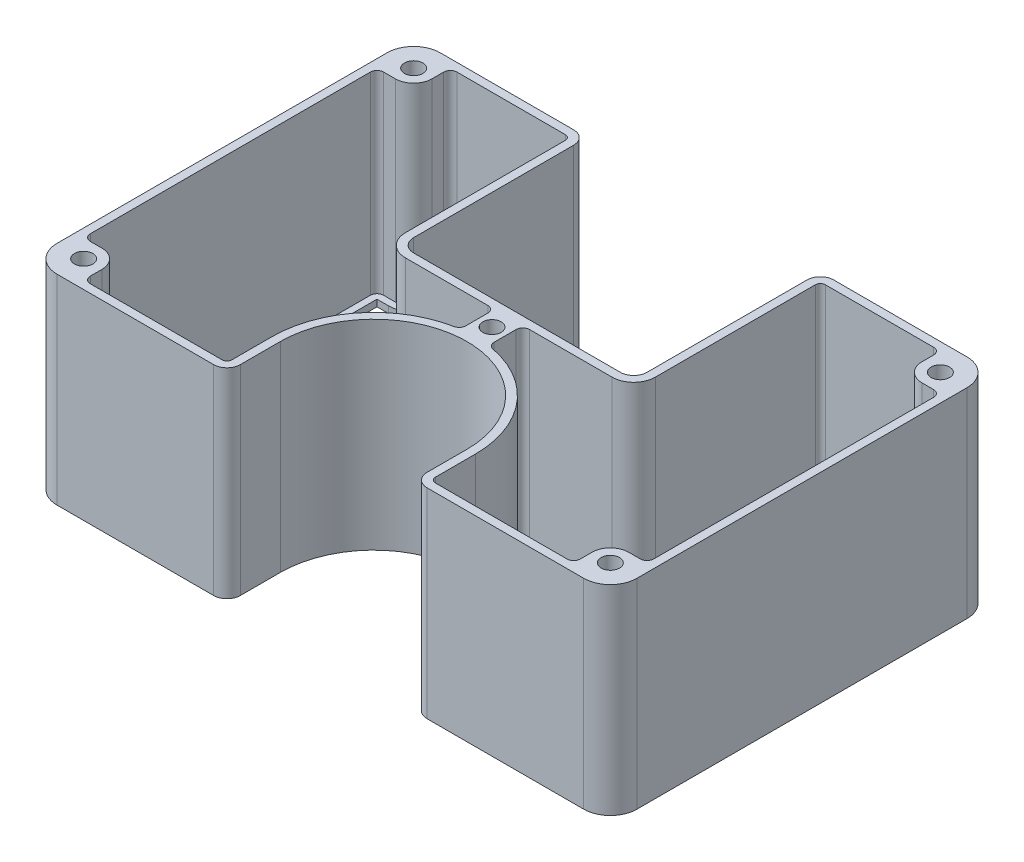
SolidWorks part; units mm, degrees
material "ABS"
ref_plane "Front Plane" through (0, 0, 0) normal (0, 0, 1) x (1, 0, 0)
ref_plane "Top Plane" through (0, 0, 0) normal (0, 1, 0) x (1, 0, 0)
ref_plane "Right Plane" through (0, 0, 0) normal (1, 0, 0) x (0, 0, -1)
sketch "Reference" plane through (0, 0, 0) normal (0, 1, 0) x (1, 0, 0)
  line L0 (-79, -96) -> (79, -96) construction
  line L1 (87, -88) -> (87, 88) construction
  line L2 (79, 96) -> (-79, 96) construction
  line L3 (-87, 88) -> (-87, -88) construction
  circle A0 centre (0, -3) radius 16.25 construction
  arc A1 (-79, -96) -> (-87, -88) centre (-79, -88) cw construction
  arc A2 (79, -96) -> (87, -88) centre (79, -88) ccw construction
  arc A3 (87, 88) -> (79, 96) centre (79, 88) ccw construction
  arc A4 (-79, 96) -> (-87, 88) centre (-79, 88) ccw construction
  circle A5 centre (-65, 78) radius 1.75 construction
  circle A6 centre (65, 78) radius 1.75 construction
  circle A7 centre (65, -78) radius 1.75 construction
  circle A8 centre (-65, -78) radius 1.75 construction
  point P6 (0, -96)
  dimension "D1" = 32.5
  dimension "D3" = 8
  dimension "D4" = 3.5
  dimension "D2" = 93
  dimension "D5" = 130
  dimension "D6" = 22
  dimension "D7" = 22
  dimension "D8" = 156
  dimension "D9" = 18
  dimension "D10" = 18
sketch "Sketch2" plane through (0, 0, 0) normal (0, 1, 0) x (1, 0, 0)
  line L0 (87, -88) -> (87, 88) construction
  line L1 (-87, 88) -> (-87, -88) construction
  line L2 (79, 96) -> (-79, 96) construction
  line L3 (87, -11) -> (87, 88)
  line L4 (-87, 88) -> (-87, -11)
  line L5 (79, 96) -> (39, 96)
  line L6 (-79, -19) -> (-32, -19)
  line L7 (79, -19) -> (32, -19)
  line L8 (-28, -15) -> (-28, -3)
  line L9 (28, -15) -> (28, -3)
  line L10 (-35, 92) -> (-35, 44)
  line L11 (-31, 40) -> (31, 40)
  line L12 (35, 44) -> (35, 92)
  line L13 (-39, 96) -> (-79, 96)
  line L14 (-39, 93.5) -> (-71.5, 93.5)
  line L15 (-84.5, 80.5) -> (-84.5, -3.5)
  line L16 (-71.5, -16.5) -> (-32, -16.5)
  line L17 (-30.5, -15) -> (-30.5, -3)
  line L18 (30.5, -15) -> (30.5, -3)
  line L19 (71.5, -16.5) -> (32, -16.5)
  line L20 (84.5, -3.5) -> (84.5, 80.5)
  line L21 (71.5, 93.5) -> (39, 93.5)
  line L22 (37.5, 44) -> (37.5, 92)
  line L23 (-31, 37.5) -> (-6.25, 37.5)
  line L24 (-37.5, 92) -> (-37.5, 44)
  line L25 (-79, 82.5) -> (-82.5, 82.5)
  line L26 (-73.5, 88) -> (-73.5, 91.5)
  line L27 (-39, 93.5) -> (-79, 93.5) construction
  line L28 (-84.5, 88) -> (-84.5, -11) construction
  line L29 (73.5, 88) -> (73.5, 91.5)
  line L30 (79, 82.5) -> (82.5, 82.5)
  line L31 (84.5, -11) -> (84.5, 88) construction
  line L32 (79, 93.5) -> (39, 93.5) construction
  line L33 (-79, -5.5) -> (-82.5, -5.5)
  line L34 (-73.5, -11) -> (-73.5, -14.5)
  line L35 (-79, -16.5) -> (-32, -16.5) construction
  line L36 (79, -5.5) -> (82.5, -5.5)
  line L37 (73.5, -11) -> (73.5, -14.5)
  line L38 (79, -16.5) -> (32, -16.5) construction
  line L39 (-4.25, 35.5) -> (-4.25, 28.8934)
  line L40 (4.25, 35.5) -> (4.25, 28.8934)
  line L41 (6.25, 37.5) -> (31, 37.5)
  line L42 (-31, 37.5) -> (31, 37.5) construction
  arc A0 (87, -11) -> (79, -19) centre (79, -11) cw
  arc A1 (87, 88) -> (79, 96) centre (79, 88) ccw construction
  arc A2 (-79, 96) -> (-87, 88) centre (-79, 88) ccw construction
  arc A4 (87, 88) -> (79, 96) centre (79, 88) ccw
  arc A5 (-79, 96) -> (-87, 88) centre (-79, 88) ccw
  arc A6 (-87, -11) -> (-79, -19) centre (-79, -11) ccw
  circle A7 centre (0, -3) radius 25 construction
  arc A8 (-28, -3) -> (28, -3) centre (0, -3) cw
  arc A9 (31, 40) -> (35, 44) centre (31, 44) ccw
  arc A10 (-35, 44) -> (-31, 40) centre (-31, 44) ccw
  arc A11 (35, 92) -> (39, 96) centre (39, 92) cw
  arc A12 (-35, 92) -> (-39, 96) centre (-39, 92) ccw
  arc A13 (32, -19) -> (28, -15) centre (32, -15) cw
  arc A14 (-32, -19) -> (-28, -15) centre (-32, -15) ccw
  arc A17 (-32, -16.5) -> (-30.5, -15) centre (-32, -15) ccw
  arc A18 (-30.5, -3) -> (-5.8654, 26.9307) centre (0, -3) cw
  arc A19 (32, -16.5) -> (30.5, -15) centre (32, -15) cw
  arc A22 (37.5, 92) -> (39, 93.5) centre (39, 92) cw
  arc A23 (31, 37.5) -> (37.5, 44) centre (31, 44) ccw
  arc A24 (-37.5, 44) -> (-31, 37.5) centre (-31, 44) ccw
  arc A25 (-37.5, 92) -> (-39, 93.5) centre (-39, 92) ccw
  circle A26 centre (-79, 88) radius 2.75
  circle A27 centre (79, 88) radius 2.75
  circle A28 centre (79, -11) radius 2.75
  circle A29 centre (-79, -11) radius 2.75
  arc A31 (-79, 82.5) -> (-73.5, 88) centre (-79, 88) ccw
  arc A32 (73.5, 88) -> (79, 82.5) centre (79, 88) ccw
  arc A33 (79, -5.5) -> (73.5, -11) centre (79, -11) ccw
  arc A34 (-73.5, -11) -> (-79, -5.5) centre (-79, -11) ccw
  arc A35 (-79, 93.5) -> (-84.5, 88) centre (-79, 88) ccw construction
  arc A36 (84.5, 88) -> (79, 93.5) centre (79, 88) ccw construction
  arc A37 (-84.5, -11) -> (-79, -16.5) centre (-79, -11) ccw construction
  arc A38 (84.5, -11) -> (79, -16.5) centre (79, -11) cw construction
  arc A39 (82.5, 82.5) -> (84.5, 80.5) centre (82.5, 80.5) cw
  arc A40 (73.5, 91.5) -> (71.5, 93.5) centre (71.5, 91.5) ccw
  arc A41 (-73.5, 91.5) -> (-71.5, 93.5) centre (-71.5, 91.5) cw
  arc A42 (-82.5, 82.5) -> (-84.5, 80.5) centre (-82.5, 80.5) ccw
  arc A43 (82.5, -5.5) -> (84.5, -3.5) centre (82.5, -3.5) ccw
  arc A44 (73.5, -14.5) -> (71.5, -16.5) centre (71.5, -14.5) cw
  arc A45 (-73.5, -14.5) -> (-71.5, -16.5) centre (-71.5, -14.5) ccw
  arc A46 (-82.5, -5.5) -> (-84.5, -3.5) centre (-82.5, -3.5) cw
  circle A47 centre (0, 32.5) radius 2.75
  arc A48 (5.8654, 26.9307) -> (30.5, -3) centre (0, -3) cw
  arc A49 (-30.5, -3) -> (30.5, -3) centre (0, -3) cw construction
  arc A50 (4.25, 35.5) -> (6.25, 37.5) centre (6.25, 35.5) cw
  arc A51 (4.25, 28.8934) -> (5.8654, 26.9307) centre (6.25, 28.8934) ccw
  arc A52 (-4.25, 28.8934) -> (-5.8654, 26.9307) centre (-6.25, 28.8934) cw
  arc A53 (-4.25, 35.5) -> (-6.25, 37.5) centre (-6.25, 35.5) ccw
  point P0 (0, -3)
  point P35 (-35, 96)
  point P38 (28, -19)
  point P41 (-28, -19)
  point P121 (4.25, 37.5)
  point P124 (4.25, 27.2024)
  point P129 (0, 25)
  point P131 (0, 40)
  dimension "D2" = 8
  dimension "D3" = 4
  dimension "D6" = 2
  dimension "D7" = 2
  dimension "D17" = 5.5
  dimension "D1" = 56
  dimension "D4" = 70
  dimension "D9" = 4.25
  dimension "D10" = 4.25
  dimension "D11" = 15
  dimension "D8" = 7.5
  dimension "D12" = 115
  dimension "D13" = 8
  dimension "D14" = 8
  dimension "D15" = 99
  dimension "D16" = 44
  dimension "D18" = 51.5
  dimension "D5" = 2.5
extrude "Boss-Extrude1" add sketch "Sketch2" along normal blind 60
sketch "Sketch3" plane through (0, 0, 0) normal (0, -1, 0) x (1, 0, 0)
  line L22 (71.5, 14.5) -> (32.5, 14.5)
  line L23 (71.5, 11) -> (71.5, 14.5)
  line L24 (82.5, 3.5) -> (79, 3.5)
  line L25 (82.5, -80.5) -> (82.5, 3.5)
  line L26 (79, -80.5) -> (82.5, -80.5)
  line L27 (71.5, -91.5) -> (71.5, -88)
  line L28 (39.5, -91.5) -> (71.5, -91.5)
  line L29 (39.5, -44) -> (39.5, -91.5)
  line L30 (6.25, -35.5) -> (31, -35.5)
  line L31 (6.25, -28.8934) -> (6.25, -35.5)
  line L32 (71.5, 14.5) -> (32.5, 14.5)
  line L33 (71.5, 11) -> (71.5, 14.5)
  line L34 (82.5, 3.5) -> (79, 3.5)
  line L35 (82.5, -80.5) -> (82.5, 3.5)
  line L36 (79, -80.5) -> (82.5, -80.5)
  line L37 (71.5, -91.5) -> (71.5, -88)
  line L38 (39.5, -91.5) -> (71.5, -91.5)
  line L39 (39.5, -44) -> (39.5, -91.5)
  line L40 (6.25, -35.5) -> (31, -35.5)
  line L41 (6.25, -28.8934) -> (6.25, -35.5)
  line L42 (30.5, 15) -> (30.5, 3)
  line L43 (71.5, 16.5) -> (32, 16.5)
  line L44 (73.5, 11) -> (73.5, 14.5)
  line L45 (-39.5, -91.5) -> (-39.5, -44)
  line L46 (-71.5, -91.5) -> (-39.5, -91.5)
  line L47 (-71.5, -88) -> (-71.5, -91.5)
  line L48 (-82.5, -80.5) -> (-79, -80.5)
  line L49 (-82.5, 3.5) -> (-82.5, -80.5)
  line L50 (-79, 3.5) -> (-82.5, 3.5)
  line L51 (-71.5, 14.5) -> (-71.5, 11)
  line L52 (-32.5, 14.5) -> (-71.5, 14.5)
  line L53 (-6.25, -35.5) -> (-6.25, -28.8934)
  line L54 (-31, -35.5) -> (-6.25, -35.5)
  line L55 (-39.5, -91.5) -> (-39.5, -44)
  line L56 (-71.5, -91.5) -> (-39.5, -91.5)
  line L57 (-71.5, -88) -> (-71.5, -91.5)
  line L58 (-82.5, -80.5) -> (-79, -80.5)
  line L59 (-82.5, 3.5) -> (-82.5, -80.5)
  line L60 (-79, 3.5) -> (-82.5, 3.5)
  line L61 (-71.5, 14.5) -> (-71.5, 11)
  line L62 (-32.5, 14.5) -> (-71.5, 14.5)
  line L63 (-6.25, -35.5) -> (-6.25, -28.8934)
  line L64 (-31, -35.5) -> (-6.25, -35.5)
  line L65 (-37.5, -92) -> (-37.5, -44)
  line L66 (-71.5, -93.5) -> (-39, -93.5)
  line L67 (-73.5, -88) -> (-73.5, -91.5)
  line L68 (-82.5, -82.5) -> (-79, -82.5)
  line L69 (-84.5, 3.5) -> (-84.5, -80.5)
  line L70 (-79, 5.5) -> (-82.5, 5.5)
  line L71 (-73.5, 14.5) -> (-73.5, 11)
  line L72 (-32, 16.5) -> (-71.5, 16.5)
  line L73 (-30.5, 3) -> (-30.5, 15)
  line L74 (-4.25, -35.5) -> (-4.25, -28.8934)
  line L75 (-31, -37.5) -> (-6.25, -37.5)
  line L76 (-37.5, -92) -> (-37.5, -44)
  line L77 (-71.5, -93.5) -> (-39, -93.5)
  line L78 (-73.5, -88) -> (-73.5, -91.5)
  line L79 (-82.5, -82.5) -> (-79, -82.5)
  line L80 (-84.5, 3.5) -> (-84.5, -80.5)
  line L81 (-79, 5.5) -> (-82.5, 5.5)
  line L82 (-73.5, 14.5) -> (-73.5, 11)
  line L83 (-32, 16.5) -> (-71.5, 16.5)
  line L84 (-30.5, 3) -> (-30.5, 15)
  line L85 (-4.25, -35.5) -> (-4.25, -28.8934)
  line L86 (-31, -37.5) -> (-6.25, -37.5)
  line L87 (82.5, 5.5) -> (79, 5.5)
  line L88 (84.5, -80.5) -> (84.5, 3.5)
  line L89 (79, -82.5) -> (82.5, -82.5)
  line L90 (73.5, -91.5) -> (73.5, -88)
  line L91 (39, -93.5) -> (71.5, -93.5)
  line L92 (37.5, -44) -> (37.5, -92)
  line L93 (6.25, -37.5) -> (31, -37.5)
  line L94 (4.25, -28.8934) -> (4.25, -35.5)
  line L95 (30.5, 15) -> (30.5, 3)
  line L96 (71.5, 16.5) -> (32, 16.5)
  line L97 (73.5, 11) -> (73.5, 14.5)
  line L98 (82.5, 5.5) -> (79, 5.5)
  line L99 (84.5, -80.5) -> (84.5, 3.5)
  line L100 (79, -82.5) -> (82.5, -82.5)
  line L101 (73.5, -91.5) -> (73.5, -88)
  line L102 (39, -93.5) -> (71.5, -93.5)
  line L103 (37.5, -44) -> (37.5, -92)
  line L104 (6.25, -37.5) -> (31, -37.5)
  line L105 (4.25, -28.8934) -> (4.25, -35.5)
  line L106 (-32.5, 3) -> (-32.5, 14.5)
  line L107 (-32.5, 3) -> (-32.5, 14.5)
  line L108 (32.5, 14.5) -> (32.5, 3)
  line L109 (32.5, 14.5) -> (32.5, 3)
  arc A24 (6.25, -28.8934) -> (32.5, 3) centre (0, 3) ccw
  arc A25 (71.5, 11) -> (79, 3.5) centre (79, 11) ccw
  arc A26 (79, -80.5) -> (71.5, -88) centre (79, -88) ccw
  arc A27 (39.5, -44) -> (31, -35.5) centre (31, -44) ccw
  arc A28 (6.25, -28.8934) -> (32.5, 3) centre (0, 3) ccw
  arc A29 (71.5, 11) -> (79, 3.5) centre (79, 11) ccw
  arc A30 (79, -80.5) -> (71.5, -88) centre (79, -88) ccw
  arc A31 (39.5, -44) -> (31, -35.5) centre (31, -44) ccw
  arc A32 (5.8654, -26.9307) -> (4.25, -28.8934) centre (6.25, -28.8934) ccw
  arc A33 (5.8654, -26.9307) -> (30.5, 3) centre (0, 3) ccw
  arc A34 (32, 16.5) -> (30.5, 15) centre (32, 15) ccw
  arc A35 (73.5, 14.5) -> (71.5, 16.5) centre (71.5, 14.5) ccw
  arc A36 (73.5, 11) -> (79, 5.5) centre (79, 11) ccw
  arc A37 (84.5, 3.5) -> (82.5, 5.5) centre (82.5, 3.5) ccw
  arc A38 (82.5, -82.5) -> (84.5, -80.5) centre (82.5, -80.5) ccw
  arc A39 (79, -82.5) -> (73.5, -88) centre (79, -88) ccw
  arc A40 (71.5, -93.5) -> (73.5, -91.5) centre (71.5, -91.5) ccw
  arc A41 (37.5, -92) -> (39, -93.5) centre (39, -92) ccw
  arc A42 (37.5, -44) -> (31, -37.5) centre (31, -44) ccw
  arc A43 (4.25, -35.5) -> (6.25, -37.5) centre (6.25, -35.5) ccw
  arc A44 (5.8654, -26.9307) -> (4.25, -28.8934) centre (6.25, -28.8934) ccw
  arc A45 (5.8654, -26.9307) -> (30.5, 3) centre (0, 3) ccw
  arc A46 (32, 16.5) -> (30.5, 15) centre (32, 15) ccw
  arc A47 (-71.5, -88) -> (-79, -80.5) centre (-79, -88) ccw
  arc A48 (-79, 3.5) -> (-71.5, 11) centre (-79, 11) ccw
  arc A49 (-32.5, 3) -> (-6.25, -28.8934) centre (0, 3) ccw
  arc A50 (-31, -35.5) -> (-39.5, -44) centre (-31, -44) ccw
  arc A51 (-71.5, -88) -> (-79, -80.5) centre (-79, -88) ccw
  arc A52 (-79, 3.5) -> (-71.5, 11) centre (-79, 11) ccw
  arc A53 (-32.5, 3) -> (-6.25, -28.8934) centre (0, 3) ccw
  arc A54 (-31, -35.5) -> (-39.5, -44) centre (-31, -44) ccw
  arc A55 (-39, -93.5) -> (-37.5, -92) centre (-39, -92) ccw
  arc A56 (-73.5, -91.5) -> (-71.5, -93.5) centre (-71.5, -91.5) ccw
  arc A57 (-73.5, -88) -> (-79, -82.5) centre (-79, -88) ccw
  arc A58 (-84.5, -80.5) -> (-82.5, -82.5) centre (-82.5, -80.5) ccw
  arc A59 (-82.5, 5.5) -> (-84.5, 3.5) centre (-82.5, 3.5) ccw
  arc A60 (-79, 5.5) -> (-73.5, 11) centre (-79, 11) ccw
  arc A61 (-71.5, 16.5) -> (-73.5, 14.5) centre (-71.5, 14.5) ccw
  arc A62 (-30.5, 15) -> (-32, 16.5) centre (-32, 15) ccw
  arc A63 (-30.5, 3) -> (-5.8654, -26.9307) centre (0, 3) ccw
  arc A64 (-4.25, -28.8934) -> (-5.8654, -26.9307) centre (-6.25, -28.8934) ccw
  arc A65 (-6.25, -37.5) -> (-4.25, -35.5) centre (-6.25, -35.5) ccw
  arc A66 (-31, -37.5) -> (-37.5, -44) centre (-31, -44) ccw
  arc A67 (-39, -93.5) -> (-37.5, -92) centre (-39, -92) ccw
  arc A68 (-73.5, -91.5) -> (-71.5, -93.5) centre (-71.5, -91.5) ccw
  arc A69 (-73.5, -88) -> (-79, -82.5) centre (-79, -88) ccw
  arc A70 (-84.5, -80.5) -> (-82.5, -82.5) centre (-82.5, -80.5) ccw
  arc A71 (-82.5, 5.5) -> (-84.5, 3.5) centre (-82.5, 3.5) ccw
  arc A72 (-79, 5.5) -> (-73.5, 11) centre (-79, 11) ccw
  arc A73 (-71.5, 16.5) -> (-73.5, 14.5) centre (-71.5, 14.5) ccw
  arc A74 (-30.5, 15) -> (-32, 16.5) centre (-32, 15) ccw
  arc A75 (-30.5, 3) -> (-5.8654, -26.9307) centre (0, 3) ccw
  arc A76 (-4.25, -28.8934) -> (-5.8654, -26.9307) centre (-6.25, -28.8934) ccw
  arc A77 (-6.25, -37.5) -> (-4.25, -35.5) centre (-6.25, -35.5) ccw
  arc A78 (-31, -37.5) -> (-37.5, -44) centre (-31, -44) ccw
  arc A79 (73.5, 14.5) -> (71.5, 16.5) centre (71.5, 14.5) ccw
  arc A80 (73.5, 11) -> (79, 5.5) centre (79, 11) ccw
  arc A81 (84.5, 3.5) -> (82.5, 5.5) centre (82.5, 3.5) ccw
  arc A82 (82.5, -82.5) -> (84.5, -80.5) centre (82.5, -80.5) ccw
  arc A83 (79, -82.5) -> (73.5, -88) centre (79, -88) ccw
  arc A84 (71.5, -93.5) -> (73.5, -91.5) centre (71.5, -91.5) ccw
  arc A85 (37.5, -92) -> (39, -93.5) centre (39, -92) ccw
  arc A86 (37.5, -44) -> (31, -37.5) centre (31, -44) ccw
  arc A87 (4.25, -35.5) -> (6.25, -37.5) centre (6.25, -35.5) ccw
  dimension "D1" = 2
  dimension "D2" = 0
  dimension "D3" = 2
  dimension "D4" = 0
extrude "Boss-Extrude2" add sketch "Sketch3" against normal blind 2
sketch "Sketch8" plane through (0, 60, 0) normal (0, 1, 0) x (1, 0, 0)
  line L22 (84.5, -11) -> (84.5, 88)
  line L23 (79, 93.5) -> (39, 93.5)
  line L24 (37.5, 92) -> (37.5, 44)
  line L25 (31, 37.5) -> (-31, 37.5)
  line L26 (-37.5, 44) -> (-37.5, 92)
  line L27 (-39, 93.5) -> (-79, 93.5)
  line L28 (-84.5, 88) -> (-84.5, -11)
  line L29 (-79, -16.5) -> (-32, -16.5)
  line L30 (-30.5, -15) -> (-30.5, -3)
  line L31 (30.5, -3) -> (30.5, -15)
  line L32 (32, -16.5) -> (79, -16.5)
  line L33 (84.5, -11) -> (84.5, 88)
  line L34 (79, 93.5) -> (39, 93.5)
  line L35 (37.5, 92) -> (37.5, 44)
  line L36 (31, 37.5) -> (-31, 37.5)
  line L37 (-37.5, 44) -> (-37.5, 92)
  line L38 (-39, 93.5) -> (-79, 93.5)
  line L39 (-84.5, 88) -> (-84.5, -11)
  line L40 (-79, -16.5) -> (-32, -16.5)
  line L41 (-30.5, -15) -> (-30.5, -3)
  line L42 (30.5, -3) -> (30.5, -15)
  line L43 (32, -16.5) -> (79, -16.5)
  arc A22 (79, -16.5) -> (84.5, -11) centre (79, -11) ccw
  arc A23 (84.5, 88) -> (79, 93.5) centre (79, 88) ccw
  arc A24 (39, 93.5) -> (37.5, 92) centre (39, 92) ccw
  arc A25 (31, 37.5) -> (37.5, 44) centre (31, 44) ccw
  arc A26 (-37.5, 44) -> (-31, 37.5) centre (-31, 44) ccw
  arc A27 (-37.5, 92) -> (-39, 93.5) centre (-39, 92) ccw
  arc A28 (-79, 93.5) -> (-84.5, 88) centre (-79, 88) ccw
  arc A29 (-84.5, -11) -> (-79, -16.5) centre (-79, -11) ccw
  arc A30 (-32, -16.5) -> (-30.5, -15) centre (-32, -15) ccw
  arc A31 (30.5, -3) -> (-30.5, -3) centre (0, -3) ccw
  arc A32 (30.5, -15) -> (32, -16.5) centre (32, -15) ccw
  arc A33 (79, -16.5) -> (84.5, -11) centre (79, -11) ccw
  arc A34 (84.5, 88) -> (79, 93.5) centre (79, 88) ccw
  arc A35 (39, 93.5) -> (37.5, 92) centre (39, 92) ccw
  arc A36 (31, 37.5) -> (37.5, 44) centre (31, 44) ccw
  arc A37 (-37.5, 44) -> (-31, 37.5) centre (-31, 44) ccw
  arc A38 (-37.5, 92) -> (-39, 93.5) centre (-39, 92) ccw
  arc A39 (-79, 93.5) -> (-84.5, 88) centre (-79, 88) ccw
  arc A40 (-84.5, -11) -> (-79, -16.5) centre (-79, -11) ccw
  arc A41 (-32, -16.5) -> (-30.5, -15) centre (-32, -15) ccw
  arc A42 (30.5, -3) -> (-30.5, -3) centre (0, -3) ccw
  arc A43 (30.5, -15) -> (32, -16.5) centre (32, -15) ccw
  dimension "D1" = 2.5
equation "\"D10@Sketch2\"=\"D9@Sketch2\""
equation "\"D8@Sketch2\"=\"D11@Sketch2\"/2"
